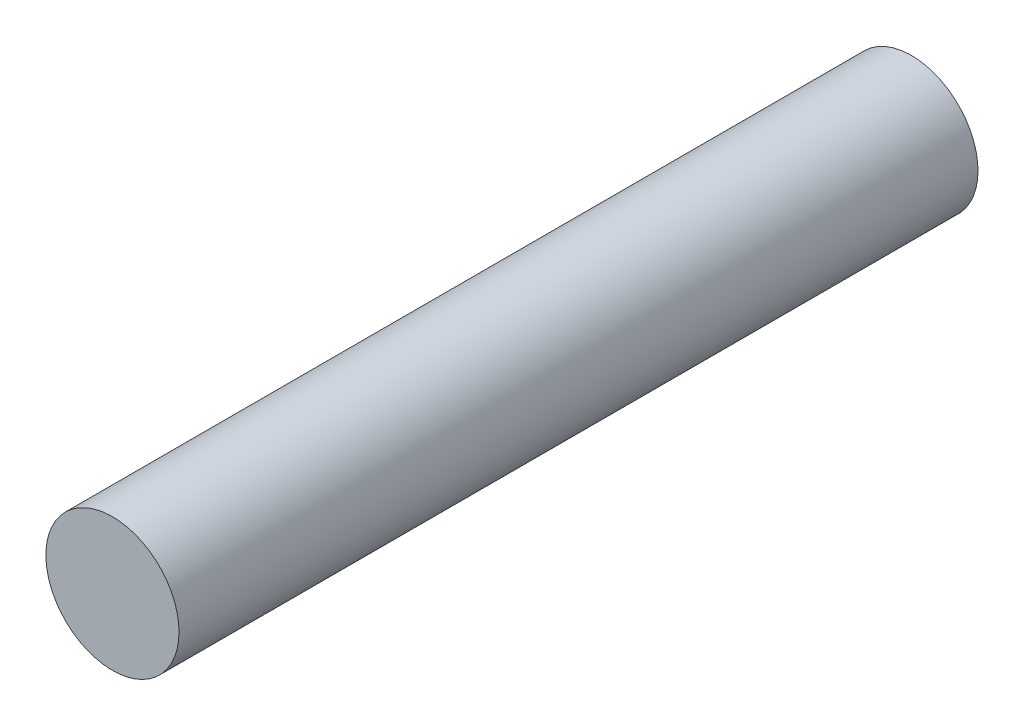
SolidWorks part; units mm, degrees
ref_plane "Front Plane" through (0, 0, 0) normal (0, 0, 1) x (1, 0, 0)
ref_plane "Top Plane" through (0, 0, 0) normal (0, 1, 0) x (1, 0, 0)
ref_plane "Right Plane" through (0, 0, 0) normal (1, 0, 0) x (0, 0, -1)
sketch "Sketch1" plane through (0, 0, 0) normal (0, 0, 1) x (1, 0, 0)
  circle A0 centre (0, 0) radius 1
  dimension "D1" = 2
extrude "Boss-Extrude1" add sketch "Sketch1" along normal blind 13
sketch "Sketch2" plane through (0, 0, 13) normal (0, 0, 1) x (1, 0, 0)
  circle A0 centre (0, 0) radius 1
extrude "Cut-Extrude1" cut sketch "Sketch2" against normal blind 1
